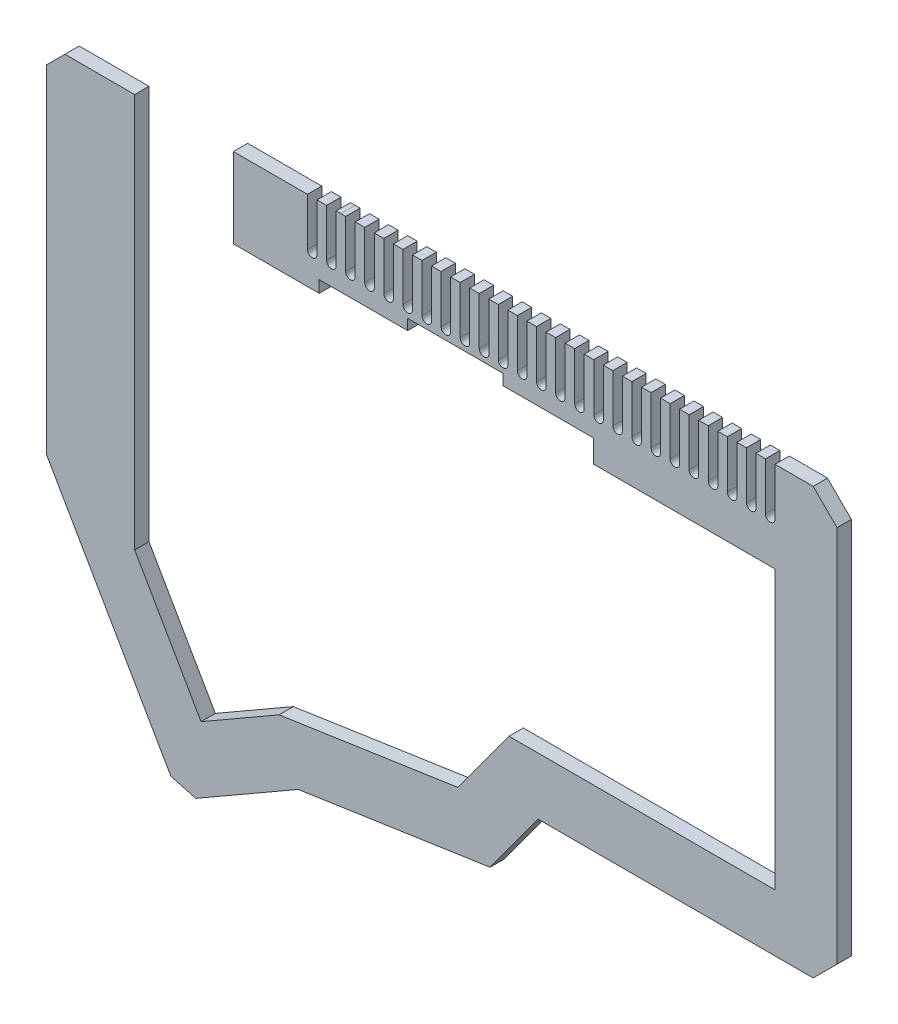
SolidWorks part; units mm, degrees
ref_plane "Plan de face" through (0, 0, 0) normal (0, 0, 1) x (1, 0, 0)
ref_plane "Plan de dessus" through (0, 0, 0) normal (0, 1, 0) x (1, 0, 0)
ref_plane "Plan de droite" through (0, 0, 0) normal (1, 0, 0) x (0, 0, -1)
sketch "Esquisse1" plane through (0, 0, 0) normal (0, 0, 1) x (1, 0, 0)
  line L0 (-117.3419, -15.4198) -> (-103.3409, -15.4198) construction
  line L1 (-103.3409, -15.4198) -> (-103.3409, -29.4208) construction
  line L2 (-103.3409, -29.4208) -> (-117.3419, -29.4208) construction
  line L3 (-117.3419, -29.4208) -> (-117.3419, -15.4198) construction
  line L4 (-98.3406, -27.0457) -> (-98.3406, -13.0447) construction
  line L5 (-98.3406, -13.0447) -> (-84.3396, -13.0447) construction
  line L6 (-84.3396, -13.0447) -> (-84.3396, -27.0457) construction
  line L7 (-84.3396, -27.0457) -> (-98.3406, -27.0457) construction
  line L8 (-79.3392, -24.6705) -> (-79.3392, -10.6695) construction
  line L9 (-79.3392, -10.6695) -> (-65.3382, -10.6695) construction
  line L10 (-65.3382, -10.6695) -> (-65.3382, -24.6705) construction
  line L11 (-65.3382, -24.6705) -> (-79.3392, -24.6705) construction
  line L12 (-60.3379, -27.0457) -> (-60.3379, -13.0447) construction
  line L13 (-60.3379, -13.0447) -> (-46.3369, -13.0447) construction
  line L14 (-46.3369, -13.0447) -> (-46.3369, -27.0457) construction
  line L15 (-46.3369, -27.0457) -> (-60.3379, -27.0457) construction
  line L16 (-41.3365, -31.796) -> (-41.3365, -17.795) construction
  line L17 (-41.3365, -17.795) -> (-27.3355, -17.795) construction
  line L18 (-27.3355, -17.795) -> (-27.3355, -31.796) construction
  line L19 (-27.3355, -31.796) -> (-41.3365, -31.796) construction
  line L20 (-22.3347, -31.796) -> (-22.3347, -17.795) construction
  line L21 (-22.3347, -17.795) -> (-8.3337, -17.795) construction
  line L22 (-8.3337, -17.795) -> (-8.3337, -31.796) construction
  line L23 (-8.3337, -31.796) -> (-22.3347, -31.796) construction
  line L24 (-117.3419, -34.4212) -> (-103.3409, -34.4212) construction
  line L25 (-103.3409, -34.4212) -> (-103.3409, -48.4222) construction
  line L26 (-103.3409, -48.4222) -> (-117.3419, -48.4222) construction
  line L27 (-117.3419, -48.4222) -> (-117.3419, -34.4212) construction
  line L28 (-98.3406, -32.046) -> (-84.3396, -32.046) construction
  line L29 (-84.3396, -32.046) -> (-84.3396, -46.047) construction
  line L30 (-84.3396, -46.047) -> (-98.3406, -46.047) construction
  line L31 (-98.3406, -46.047) -> (-98.3406, -32.046) construction
  line L32 (-79.3392, -29.6709) -> (-65.3382, -29.6709) construction
  line L33 (-65.3382, -29.6709) -> (-65.3382, -43.6718) construction
  line L34 (-65.3382, -43.6718) -> (-79.3392, -43.6718) construction
  line L35 (-79.3392, -43.6718) -> (-79.3392, -29.6709) construction
  line L36 (-60.3379, -32.046) -> (-46.3369, -32.046) construction
  line L37 (-46.3369, -32.046) -> (-46.3369, -46.047) construction
  line L38 (-46.3369, -46.047) -> (-60.3379, -46.047) construction
  line L39 (-60.3379, -46.047) -> (-60.3379, -32.046) construction
  line L40 (-41.3365, -36.7964) -> (-27.3355, -36.7964) construction
  line L41 (-27.3355, -36.7964) -> (-27.3355, -50.7973) construction
  line L42 (-27.3355, -50.7973) -> (-41.3365, -50.7973) construction
  line L43 (-41.3365, -50.7973) -> (-41.3365, -36.7964) construction
  line L44 (-22.3347, -36.7964) -> (-8.3337, -36.7964) construction
  line L45 (-8.3337, -36.7964) -> (-8.3337, -50.7973) construction
  line L46 (-8.3337, -50.7973) -> (-22.3347, -50.7973) construction
  line L47 (-22.3347, -50.7973) -> (-22.3347, -36.7964) construction
  line L48 (-22.3347, -55.7977) -> (-8.3337, -55.7977) construction
  line L49 (-8.3337, -55.7977) -> (-8.3337, -69.7987) construction
  line L50 (-8.3337, -69.7987) -> (-22.3347, -69.7987) construction
  line L51 (-22.3347, -69.7987) -> (-22.3347, -55.7977) construction
  line L52 (-41.3365, -55.7977) -> (-27.3355, -55.7977) construction
  line L53 (-27.3355, -55.7977) -> (-27.3355, -69.7987) construction
  line L54 (-27.3355, -69.7987) -> (-41.3365, -69.7987) construction
  line L55 (-41.3365, -69.7987) -> (-41.3365, -55.7977) construction
  line L56 (-60.3379, -51.0474) -> (-46.3369, -51.0474) construction
  line L57 (-46.3369, -51.0474) -> (-46.3369, -65.0484) construction
  line L58 (-46.3369, -65.0484) -> (-60.3379, -65.0484) construction
  line L59 (-60.3379, -65.0484) -> (-60.3379, -51.0474) construction
  line L60 (-79.3392, -48.6722) -> (-65.3382, -48.6722) construction
  line L61 (-65.3382, -48.6722) -> (-65.3382, -62.6732) construction
  line L62 (-65.3382, -62.6732) -> (-79.3392, -62.6732) construction
  line L63 (-79.3392, -62.6732) -> (-79.3392, -48.6722) construction
  line L64 (-98.3406, -51.0474) -> (-84.3396, -51.0474) construction
  line L65 (-84.3396, -51.0474) -> (-84.3396, -65.0484) construction
  line L66 (-84.3396, -65.0484) -> (-98.3406, -65.0484) construction
  line L67 (-98.3406, -65.0484) -> (-98.3406, -51.0474) construction
  line L68 (-117.3419, -53.4225) -> (-103.3409, -53.4225) construction
  line L69 (-103.3409, -53.4225) -> (-103.3409, -67.4235) construction
  line L70 (-103.3409, -67.4235) -> (-117.3419, -67.4235) construction
  line L71 (-117.3419, -67.4235) -> (-117.3419, -53.4225) construction
  line L72 (-88.8399, -70.6738) -> (-74.8389, -70.6738) construction
  line L73 (-74.8389, -70.6738) -> (-74.8389, -84.6747) construction
  line L74 (-74.8389, -84.6747) -> (-88.8399, -84.6747) construction
  line L75 (-88.8399, -84.6747) -> (-88.8399, -70.6738) construction
  line L76 (-111.4175, -75.4665) -> (-97.8899, -71.8565) construction
  line L77 (-97.8899, -71.8565) -> (-94.28, -85.3841) construction
  line L78 (-94.28, -85.3841) -> (-107.8075, -88.9941) construction
  line L79 (-107.8075, -88.9941) -> (-111.4175, -75.4665) construction
  line L80 (-134.6581, -81.5997) -> (-122.5281, -74.6075) construction
  line L81 (-122.5281, -74.6075) -> (-115.5359, -86.7375) construction
  line L82 (-115.5359, -86.7375) -> (-127.6659, -93.7297) construction
  line L83 (-127.6659, -93.7297) -> (-134.6581, -81.5997) construction
  line L86 (-6.7979, -71.9336) -> (-62.0853, -71.9336) construction
  line L89 (-72.824, -86.6446) -> (-62.0853, -71.9336) construction
  line L96 (-109.7697, -91.4639) -> (-73.0906, -86.6918) construction
  line L97 (-124.664, -99.8297) -> (-110.3971, -91.5881) construction
  line L98 (-139.9408, -76.5013) -> (-126.7151, -99.4281) construction
  line L99 (-119.8527, -15.5421) -> (-139.6028, -15.5421) construction
  line L100 (-100.8528, -13.2921) -> (-118.8527, -13.2921) construction
  line L101 (-63.8455, -8.5421) -> (-80.8528, -8.5421) construction
  line L102 (-44.8455, -10.792) -> (-62.8485, -10.792) construction
  line L103 (-25.8456, -15.5421) -> (-43.8486, -15.5421) construction
  line L104 (-6.8456, -15.5421) -> (-23.8529, -15.5421) construction
  line L105 (-6.2741, -71.3672) -> (-6.2741, -16.1136) construction
  line L106 (-23.8529, -71.9423) -> (-6.8456, -71.9423) construction
  line L107 (-61.8455, -71.9423) -> (-25.8456, -71.9423) construction
  line L108 (-72.6738, -86.4911) -> (-62.1363, -72.0583) construction
  line L109 (-140.1743, -16.1136) -> (-140.1743, -75.5958) construction
  line L110 (-134.3462, 1.5705) -> (-134.3466, -55.7217) construction
  line L111 (-134.3466, -55.7217) -> (-160.479, -70.8411) construction
  line L112 (-160.479, -70.8411) -> (-133.7613, -117.344) construction
  line L113 (-126.937, -119.1852) -> (-105.0783, -106.604) construction
  line L114 (-105.0783, -106.604) -> (-64.4097, -100.5586) construction
  line L115 (-64.4097, -100.5586) -> (-54.4636, -86.9336) construction
  line L116 (3.6609, -86.9336) -> (-54.4636, -86.9336) construction
  line L117 (8.2021, -82.3924) -> (8.2021, 1.315) construction
  line L129 (8.2021, -86.9336) -> (8.2021, -0.6796) construction
  line L130 (-48.8019, 6.3182) -> (-96.8032, 6.3209) construction
  line L131 (-115.3458, 1.5705) -> (-134.3462, 1.5705) construction
  line L132 (-160.479, -3.4295) -> (-160.479, -70.8411) construction
  line L134 (-119.3463, 4.3209) -> (-119.3464, -12.4295)
  line L135 (-119.3466, -64.3728) -> (-135.695, -73.8315) construction
  line L136 (-140.0228, -78.3428) -> (-140.0228, 4.3209)
  line L138 (-160.479, -70.8411) -> (-131.2704, -121.6794) construction
  line L139 (-131.2704, -121.6794) -> (-105.0783, -106.604) construction
  line L140 (-133.7613, -117.344) -> (-126.937, -119.1852) construction
  line L142 (8.2021, 1.315) -> (3.2021, 6.3153) construction
  line L143 (8.2021, -86.9336) -> (-54.4636, -86.9336) construction
  line L144 (8.2021, -82.3924) -> (3.6609, -86.9336) construction
  line L149 (-119.3463, 6.3209) -> (-119.3463, 1.5705) construction
  line L150 (-140.0228, 1.5705) -> (-140.0228, 6.3209) construction
  line L151 (-140.0228, 6.3209) -> (-155.479, 6.3209) construction
  line L152 (-160.479, 1.3209) -> (-160.479, -3.4295) construction
  line L153 (-155.479, 6.3209) -> (-160.479, 1.3209) construction
  line L154 (8.2021, -1.685) -> (-119.3463, -1.6779) construction
  line L155 (-146.0924, -79.8227) -> (-128.3223, -110.752) construction
  line L156 (-128.3223, -110.752) -> (-107.7547, -98.9139) construction
  line L157 (-140.0228, -78.3428) -> (-126.1111, -102.5565)
  line L158 (-126.1111, -102.5565) -> (-109.762, -93.1464)
  line L159 (-109.762, -93.1464) -> (-72.2631, -87.5722)
  line L160 (-72.2631, -87.5722) -> (-61.5772, -72.9336)
  line L161 (-5.7979, -72.9336) -> (-61.5772, -72.9336)
  line L162 (-5.7979, -72.9336) -> (-5.7979, -14.6796)
  line L163 (-5.7979, -14.6796) -> (-43.8006, -14.6796)
  line L164 (-43.8006, -14.6796) -> (-43.8006, -9.9293)
  line L165 (-43.8006, -9.9293) -> (-62.8019, -9.9293)
  line L166 (-62.8019, -9.9293) -> (-62.8019, -7.681)
  line L167 (-62.8019, -7.681) -> (-82.8032, -7.6799)
  line L168 (-82.8032, -7.6799) -> (-82.8032, -9.9293)
  line L169 (-82.8032, -9.9293) -> (-101.3458, -9.9293)
  line L170 (-101.3458, -9.9293) -> (-101.3458, -12.4295)
  line L171 (-101.3458, -12.4295) -> (-119.3464, -12.4295)
  line L172 (-120.3463, -12.4295) -> (-120.3466, -64.3728) construction
  line L173 (-119.8474, -63.5072) -> (-140.5236, -75.4699) construction
  line L174 (-107.7547, -98.9139) -> (-68.8973, -93.1378) construction
  line L175 (-68.8973, -93.1378) -> (-58.5285, -78.9336) construction
  line L176 (0.2021, -78.9336) -> (-58.5285, -78.9336) construction
  line L177 (0.2021, -78.9336) -> (0.2021, -1.6845) construction
  line L178 (-62.8016, -1.681) -> (-82.8029, -1.6799) construction
  line L179 (0.2021, -78.9336) -> (0.2021, -14.6796) construction
  line L180 (-146.0228, -76.3355) -> (-146.0228, 1.5705) construction
  line L181 (-140.0228, -76.3355) -> (-140.0228, 1.5705) construction
  line L182 (-135.695, -73.8315) -> (-140.0228, -71.3355) construction
  line L183 (2.2021, 4.3153) -> (-5.7979, 4.3158)
  line L184 (-103.7997, 4.3209) -> (-103.7979, 4.3209)
  line L185 (-103.7997, 4.3209) -> (-117.3463, 4.3209)
  line L186 (-117.3463, 4.3209) -> (-117.3463, 1.5705) construction
  line L187 (-117.3463, 1.5705) -> (-117.3466, -65.5263) construction
  line L188 (-117.3466, -65.5263) -> (-135.6934, -76.1412) construction
  line L189 (-135.6934, -76.1412) -> (-142.0228, -72.4908) construction
  line L190 (-142.0228, -72.4908) -> (-142.0228, 1.5705) construction
  line L191 (-142.0228, 1.5705) -> (-142.0228, 4.3209) construction
  line L192 (-142.0228, 4.3209) -> (-154.6506, 4.3209)
  line L193 (-154.6506, 4.3209) -> (-158.479, 0.4924)
  line L194 (-158.479, 0.4924) -> (-158.479, -3.4295)
  line L195 (-158.479, -3.4295) -> (-158.479, -70.3075)
  line L196 (-158.479, -70.3075) -> (-132.44, -115.629)
  line L197 (-132.44, -115.629) -> (-127.2163, -117.0383)
  line L198 (-127.2163, -117.0383) -> (-105.7474, -104.6815)
  line L199 (-105.7474, -104.6815) -> (-65.5316, -98.7034)
  line L200 (-65.5316, -98.7034) -> (-55.4798, -84.9336)
  line L201 (2.2021, -84.9336) -> (-55.4798, -84.9336)
  line L205 (-142.0228, 4.3209) -> (-140.0228, 4.3209)
  line L206 (-140.8899, -76.8336) -> (-119.3466, -64.3728) construction
  line L207 (-140.0228, -71.3355) -> (-140.0228, 1.5705) construction
  line L208 (-119.3463, 4.3209) -> (-117.3463, 4.3209)
  line L209 (-140.8899, -76.8336) -> (-126.1111, -102.5565) construction
  line L210 (-119.3463, 1.5705) -> (-119.3466, -64.3728) construction
  line L211 (-101.3458, -12.4295) -> (-120.3463, -12.4295) construction
  line L212 (7.2021, -0.6849) -> (7.2021, -79.9336)
  line L213 (-6.7979, 4.3158) -> (-6.7979, -5.6842) construction
  line L217 (-6.7979, -71.9336) -> (-6.7979, -15.6796) construction
  line L220 (-6.7979, -15.6796) -> (-44.8006, -15.6796) construction
  line L221 (-44.8006, -15.6796) -> (-44.8006, -10.9293) construction
  line L222 (-44.8006, -10.9293) -> (-63.8019, -10.9293) construction
  line L223 (-63.8019, -10.9293) -> (-63.8019, -8.681) construction
  line L224 (-63.8019, -8.681) -> (-81.8032, -8.68) construction
  line L225 (-81.8032, -8.68) -> (-81.8032, -10.9293) construction
  line L226 (-81.8032, -10.9293) -> (-100.3458, -10.9293) construction
  line L227 (-100.3458, -10.9293) -> (-100.3458, -13.4295) construction
  line L228 (-100.3458, -13.4295) -> (-119.3463, -13.4295) construction
  line L231 (-119.3463, -13.4295) -> (-119.3466, -64.3728) construction
  line L232 (-119.3466, -64.3728) -> (-140.0228, -76.3355) construction
  line L233 (-140.0228, -76.3355) -> (-125.7426, -101.1906) construction
  line L234 (-125.7426, -101.1906) -> (-110.0965, -92.1851) construction
  line L235 (-110.0965, -92.1851) -> (-72.824, -86.6446) construction
  line L236 (6.2021, -81.564) -> (2.8325, -84.9336) construction
  line L239 (2.8325, -84.9336) -> (-55.4798, -84.9336) construction
  line L242 (6.2021, -81.564) -> (6.2021, 0.4866) construction
  line L245 (7.2021, -79.9336) -> (2.2021, -84.9336)
  line L248 (2.2021, 4.3153) -> (7.2021, -0.6849)
  line L311 (-103.7979, 4.3209) -> (-103.7979, -5.6842)
  line L312 (-9.7979, 4.316) -> (-9.7979, -5.6842)
  line L313 (-7.7979, 4.3159) -> (-7.7979, -5.6842)
  line L314 (-5.7979, 4.3158) -> (-5.7979, -5.6842)
  line L315 (-101.7979, 4.3209) -> (-101.7979, -5.6842)
  line L316 (-99.7979, 4.3209) -> (-99.7979, -5.6842)
  line L317 (-101.7979, 4.3209) -> (-99.7979, 4.3209)
  line L318 (-97.7979, 4.3209) -> (-96.8033, 4.3209)
  line L319 (-103.7997, 4.3209) -> (-96.8033, 4.3209) construction
  line L320 (-97.7979, 4.3209) -> (-97.7979, -5.6842)
  line L321 (-95.7979, 4.3208) -> (-95.7979, -5.6842)
  line L322 (-95.7979, 4.3208) -> (-96.8033, 4.3209)
  line L323 (-91.7979, 4.3206) -> (-93.7979, 4.3207)
  line L324 (2.3736, 4.3153) -> (-96.8033, 4.3209) construction
  line L325 (-93.7979, 4.3207) -> (-93.7979, -5.6842)
  line L326 (-91.7979, 4.3206) -> (-91.7979, -5.6842)
  line L327 (-87.7979, 4.3204) -> (-89.7979, 4.3205)
  line L328 (-48.8019, 4.0707) -> (-48.8019, 6.3182) construction
  line L329 (-29.8006, 4.0707) -> (-48.8019, 4.0707) construction
  line L330 (-29.8006, -0.6796) -> (-29.8006, 4.0707) construction
  line L331 (8.2021, -0.6796) -> (-29.8006, -0.6796) construction
  line L332 (-115.3458, 4.0707) -> (-115.3458, 1.5705) construction
  line L333 (-96.8032, 4.0707) -> (-115.3458, 4.0707) construction
  line L334 (-96.8032, 6.3209) -> (-96.8032, 4.0707) construction
  line L335 (-83.7979, 4.3201) -> (-85.7979, 4.3202)
  line L336 (-79.7979, 4.3199) -> (-81.7979, 4.32)
  line L337 (-89.7979, 4.3205) -> (-89.7979, -5.6842)
  line L338 (-87.7979, 4.3204) -> (-87.7979, -5.6842)
  line L339 (-75.7979, 4.3197) -> (-77.7979, 4.3198)
  line L340 (-71.7979, 4.3195) -> (-73.7979, 4.3196)
  line L341 (-67.7979, 4.3192) -> (-69.7979, 4.3194)
  line L342 (-85.7979, 4.3202) -> (-85.7979, -5.6842)
  line L343 (-83.7979, 4.3201) -> (-83.7979, -5.6842)
  line L344 (-63.7979, 4.319) -> (-65.7979, 4.3191)
  line L345 (-59.7979, 4.3188) -> (-61.7979, 4.3189)
  line L346 (-55.7979, 4.3186) -> (-57.7979, 4.3187)
  line L347 (-81.7979, 4.32) -> (-81.7979, -5.6842)
  line L348 (-79.7979, 4.3199) -> (-79.7979, -5.6842)
  line L349 (-51.7979, 4.3183) -> (-53.7979, 4.3185)
  line L350 (-47.7979, 4.3181) -> (-49.7979, 4.3182)
  line L351 (-43.7979, 4.3179) -> (-45.7979, 4.318)
  line L352 (-77.7979, 4.3198) -> (-77.7979, -5.6842)
  line L353 (-75.7979, 4.3197) -> (-75.7979, -5.6842)
  line L354 (-39.7979, 4.3177) -> (-41.7979, 4.3178)
  line L355 (-35.7979, 4.3175) -> (-37.7979, 4.3176)
  line L356 (-31.7979, 4.3172) -> (-33.7979, 4.3173)
  line L357 (-73.7979, 4.3196) -> (-73.7979, -5.6842)
  line L358 (-71.7979, 4.3195) -> (-71.7979, -5.6842)
  line L359 (-27.7979, 4.317) -> (-29.7979, 4.3171)
  line L360 (-23.7979, 4.3168) -> (-25.7979, 4.3169)
  line L361 (-19.7979, 4.3166) -> (-21.7979, 4.3167)
  line L362 (-69.7979, 4.3194) -> (-69.7979, -5.6842)
  line L363 (-67.7979, 4.3192) -> (-67.7979, -5.6842)
  line L364 (-15.7979, 4.3163) -> (-17.7979, 4.3165)
  line L365 (-11.7979, 4.3161) -> (-13.7979, 4.3162)
  line L366 (-7.7979, 4.3159) -> (-9.7979, 4.316)
  line L367 (-65.7979, 4.3191) -> (-65.7979, -5.6842)
  line L368 (-63.7979, 4.319) -> (-63.7979, -5.6842)
  line L372 (-61.7979, 4.3189) -> (-61.7979, -5.6842)
  line L373 (-59.7979, 4.3188) -> (-59.7979, -5.6842)
  line L377 (-57.7979, 4.3187) -> (-57.7979, -5.6842)
  line L378 (-55.7979, 4.3186) -> (-55.7979, -5.6842)
  line L382 (-53.7979, 4.3185) -> (-53.7979, -5.6842)
  line L383 (-51.7979, 4.3183) -> (-51.7979, -5.6842)
  line L387 (-49.7979, 4.3182) -> (-49.7979, -5.6842)
  line L388 (-47.7979, 4.3181) -> (-47.7979, -5.6842)
  line L392 (-45.7979, 4.318) -> (-45.7979, -5.6842)
  line L393 (-43.7979, 4.3179) -> (-43.7979, -5.6842)
  line L397 (-41.7979, 4.3178) -> (-41.7979, -5.6842)
  line L398 (-39.7979, 4.3177) -> (-39.7979, -5.6842)
  line L402 (-37.7979, 4.3176) -> (-37.7979, -5.6842)
  line L403 (-35.7979, 4.3175) -> (-35.7979, -5.6842)
  line L407 (-33.7979, 4.3173) -> (-33.7979, -5.6842)
  line L408 (-31.7979, 4.3172) -> (-31.7979, -5.6842)
  line L412 (-29.7979, 4.3171) -> (-29.7979, -5.6842)
  line L413 (-27.7979, 4.317) -> (-27.7979, -5.6842)
  line L417 (-25.7979, 4.3169) -> (-25.7979, -5.6842)
  line L418 (-23.7979, 4.3168) -> (-23.7979, -5.6842)
  line L422 (-21.7979, 4.3167) -> (-21.7979, -5.6842)
  line L423 (-19.7979, 4.3166) -> (-19.7979, -5.6842)
  line L427 (-17.7979, 4.3165) -> (-17.7979, -5.6842)
  line L428 (-15.7979, 4.3163) -> (-15.7979, -5.6842)
  line L432 (-13.7979, 4.3162) -> (-13.7979, -5.6842)
  line L433 (-11.7979, 4.3161) -> (-11.7979, -5.6842)
  line L434 (3.2021, 6.3153) -> (-96.8032, 6.3209) construction
  line L435 (-103.7997, 6.3209) -> (-96.8032, 6.3209) construction
  line L436 (-103.7997, 6.3209) -> (-119.3463, 6.3209) construction
  line L437 (6.2021, 0.4866) -> (2.3736, 4.3153) construction
  circle A2 centre (0.2021, -1.6845) radius 1.6 construction
  circle A3 centre (0.2021, -1.6845) radius 3 construction
  circle A4 centre (-110.8559, -1.6784) radius 1.6 construction
  circle A5 centre (0.2021, -78.9336) radius 1.6 construction
  circle A6 centre (-68.8973, -93.1378) radius 1.6 construction
  circle A7 centre (-128.3223, -110.752) radius 1.6 construction
  circle A8 centre (-146.0924, -79.8227) radius 1.6 construction
  circle A9 centre (-146.0228, -1.6779) radius 1.6 construction
  circle A10 centre (-110.8559, -1.6784) radius 3 construction
  circle A11 centre (-146.0228, -1.6779) radius 3 construction
  circle A12 centre (-146.0924, -79.8227) radius 3 construction
  circle A13 centre (-128.3223, -110.752) radius 3 construction
  circle A14 centre (-68.8973, -93.1378) radius 3 construction
  circle A15 centre (0.2021, -78.9336) radius 3 construction
  arc A17 (-7.7979, -5.6842) -> (-5.7979, -5.6842) centre (-6.7979, -5.6842) ccw
  arc A19 (-11.7979, -5.6842) -> (-9.7979, -5.6842) centre (-10.7979, -5.6842) ccw
  arc A21 (-15.7979, -5.6842) -> (-13.7979, -5.6842) centre (-14.7979, -5.6842) ccw
  arc A23 (-19.7979, -5.6842) -> (-17.7979, -5.6842) centre (-18.7979, -5.6842) ccw
  arc A25 (-23.7979, -5.6842) -> (-21.7979, -5.6842) centre (-22.7979, -5.6842) ccw
  arc A27 (-27.7979, -5.6842) -> (-25.7979, -5.6842) centre (-26.7979, -5.6842) ccw
  arc A29 (-31.7979, -5.6842) -> (-29.7979, -5.6842) centre (-30.7979, -5.6842) ccw
  arc A31 (-35.7979, -5.6842) -> (-33.7979, -5.6842) centre (-34.7979, -5.6842) ccw
  arc A33 (-39.7979, -5.6842) -> (-37.7979, -5.6842) centre (-38.7979, -5.6842) ccw
  arc A35 (-43.7979, -5.6842) -> (-41.7979, -5.6842) centre (-42.7979, -5.6842) ccw
  arc A37 (-47.7979, -5.6842) -> (-45.7979, -5.6842) centre (-46.7979, -5.6842) ccw
  arc A39 (-51.7979, -5.6842) -> (-49.7979, -5.6842) centre (-50.7979, -5.6842) ccw
  arc A41 (-55.7979, -5.6842) -> (-53.7979, -5.6842) centre (-54.7979, -5.6842) ccw
  arc A43 (-59.7979, -5.6842) -> (-57.7979, -5.6842) centre (-58.7979, -5.6842) ccw
  arc A45 (-63.7979, -5.6842) -> (-61.7979, -5.6842) centre (-62.7979, -5.6842) ccw
  arc A47 (-67.7979, -5.6842) -> (-65.7979, -5.6842) centre (-66.7979, -5.6842) ccw
  arc A49 (-71.7979, -5.6842) -> (-69.7979, -5.6842) centre (-70.7979, -5.6842) ccw
  arc A51 (-75.7979, -5.6842) -> (-73.7979, -5.6842) centre (-74.7979, -5.6842) ccw
  arc A53 (-79.7979, -5.6842) -> (-77.7979, -5.6842) centre (-78.7979, -5.6842) ccw
  arc A55 (-83.7979, -5.6842) -> (-81.7979, -5.6842) centre (-82.7979, -5.6842) ccw
  arc A57 (-87.7979, -5.6842) -> (-85.7979, -5.6842) centre (-86.7979, -5.6842) ccw
  arc A59 (-91.7979, -5.6842) -> (-89.7979, -5.6842) centre (-90.7979, -5.6842) ccw
  arc A61 (-95.7979, -5.6842) -> (-93.7979, -5.6842) centre (-94.7979, -5.6842) ccw
  arc A63 (-99.7979, -5.6842) -> (-97.7979, -5.6842) centre (-98.7979, -5.6842) ccw
  arc A65 (-103.7979, -5.6842) -> (-101.7979, -5.6842) centre (-102.7979, -5.6842) ccw
  point P138 (-160.479, 1.5705)
  point P139 (8.2021, 6.315)
  point P150 (-160.479, 6.3209)
  point P233 (0, 0)
  point P236 (7.2021, -84.9336)
  point P237 (-6.7979, 1.7384)
  point P245 (7.2021, 4.3151)
  point P246 (-10.7979, 1.7384)
  point P253 (-14.7979, 1.7384)
  point P260 (-18.7979, 1.7384)
  point P267 (-22.7979, 1.7384)
  point P274 (-26.7979, 1.7384)
  point P281 (-30.7979, 1.7384)
  point P288 (-34.7979, 1.7384)
  point P295 (-38.7979, 1.7384)
  point P302 (-42.7979, 1.7384)
  point P309 (-46.7979, 1.7384)
  point P316 (-50.7979, 1.7384)
  point P323 (-54.7979, 1.7384)
  point P330 (-58.7979, 1.7384)
  point P337 (-62.7979, 1.7384)
  point P344 (-66.7979, 1.7384)
  point P351 (-70.7979, 1.7384)
  point P358 (-74.7979, 1.7384)
  point P365 (-78.7979, 1.7384)
  point P372 (-82.7979, 1.7384)
  point P379 (-86.7979, 1.7384)
  point P386 (-90.7979, 1.7384)
  point P393 (-94.7979, 1.7384)
  point P400 (-98.7979, 1.7384)
  point P407 (-102.7979, 1.7384)
  dimension "D3" = 3.2
  dimension "D4" = 6
  dimension "D6" = 3.2
  dimension "D7" = 3.2
  dimension "D8" = 3.2
  dimension "D9" = 3.2
  dimension "D10" = 3.2
  dimension "D15" = 3.2
  dimension "D2" = 6
  dimension "D1" = 15
  dimension "D5" = 1
  dimension "D13" = 6
extrude "Boss.-Extru.1" add sketch "Esquisse1" along normal blind 3
